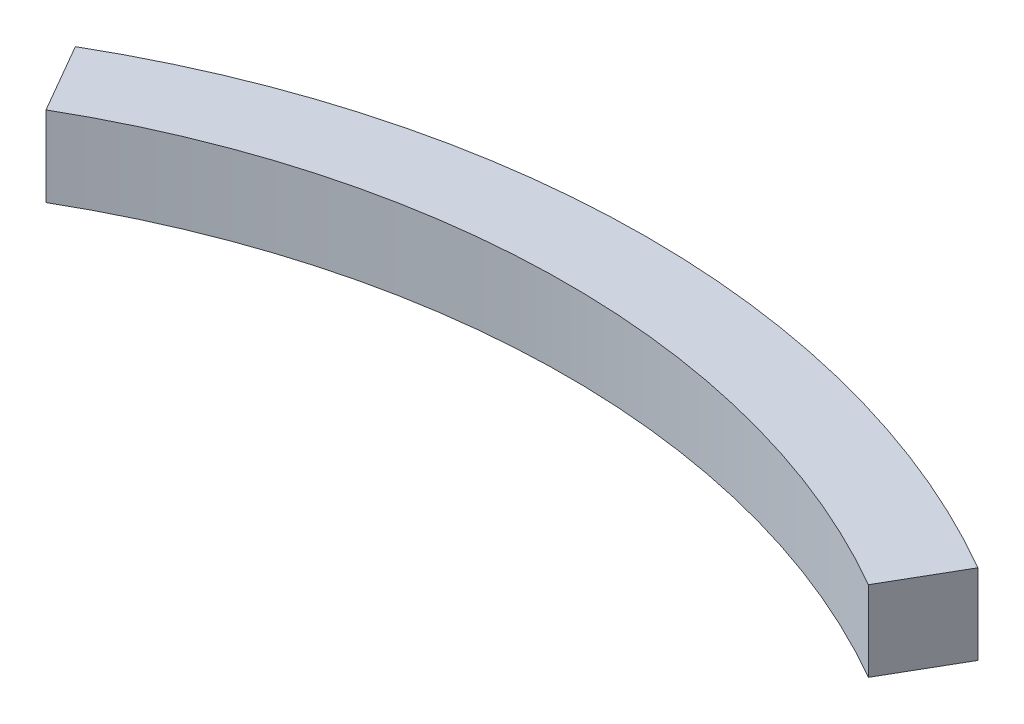
SolidWorks part; units mm, degrees
ref_plane "Спереди" through (0, 0, 0) normal (0, 0, 1) x (1, 0, 0)
ref_plane "Сверху" through (0, 0, 0) normal (0, 1, 0) x (1, 0, 0)
ref_plane "Справа" through (0, 0, 0) normal (1, 0, 0) x (0, 0, -1)
sketch "Эскиз1" plane through (0, 0, 0) normal (0, 1, 0) x (1, 0, 0)
  line L0 (5.125, 8.8768) -> (5.625, 9.7428)
  line L1 (-5.125, 8.8768) -> (-5.625, 9.7428)
  line L2 (0, 0) -> (-12.6878, 21.9759) construction
  line L3 (0, 0) -> (12.4063, 21.4884) construction
  line L4 (0, -20.1136) -> (0, 6.836) construction
  arc A0 (-5.625, 9.7428) -> (5.625, 9.7428) centre (0, 0) cw
  arc A1 (-5.125, 8.8768) -> (5.125, 8.8768) centre (0, 0) cw
  dimension "D2" = 11.25
  dimension "D3" = 10.25
  dimension "D4" = 30
  dimension "D5" = 30
extrude "Вытянуть1" add sketch "Эскиз1" along normal blind 1
